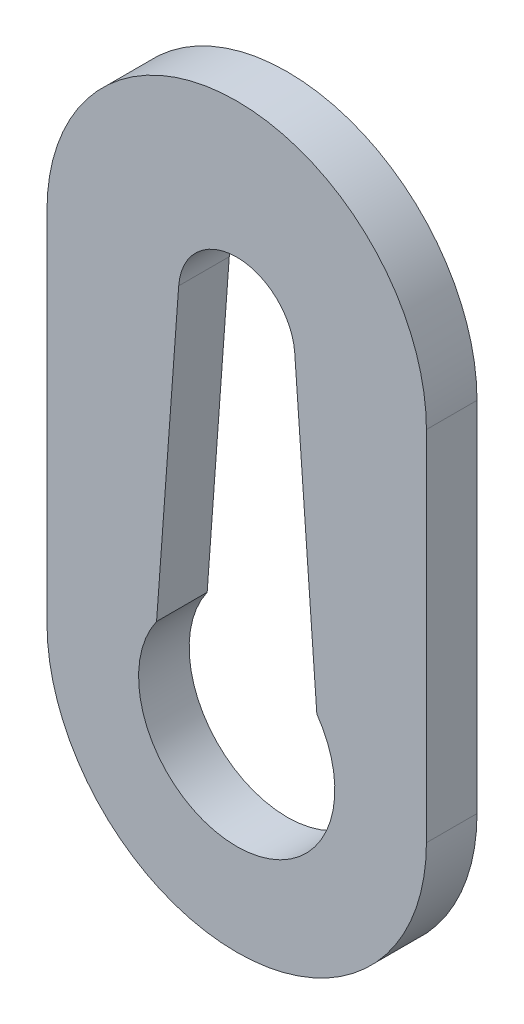
SolidWorks part; units mm, degrees
ref_plane "Front Plane" through (0, 0, 0) normal (0, 0, 1) x (1, 0, 0)
ref_plane "Top Plane" through (0, 0, 0) normal (0, 1, 0) x (1, 0, 0)
ref_plane "Right Plane" through (0, 0, 0) normal (1, 0, 0) x (0, 0, -1)
sketch "Sketch1" plane through (0, 0, 0) normal (0, 0, 1) x (1, 0, 0)
  line L0 (78.2916, 74.0996) -> (77.4175, 62.1716)
  line L1 (82.8793, 74.0996) -> (83.7534, 62.1716)
  line L3 (73.0854, 59.9315) -> (73.0854, 74.0776)
  line L5 (88.0854, 59.9315) -> (88.0854, 74.0776)
  arc A0 (73.0854, 74.0776) -> (88.0854, 74.0776) centre (80.5854, 74.0776) cw
  arc A1 (73.0854, 59.9315) -> (88.0854, 59.9315) centre (80.5854, 59.9315) ccw
  circle A2 centre (80.5854, 72.5315) radius 0.8
  circle A3 centre (80.5854, 59.9315) radius 1.85
  arc A5 (77.4175, 62.1716) -> (83.7534, 62.1716) centre (80.5854, 59.9324) ccw
  arc A6 (78.2916, 74.0996) -> (82.8793, 74.0996) centre (80.5854, 73.9315) cw
  point P21 (80.5854, 76.2315)
  point P23 (78.2916, 74.0996)
  point P26 (82.8793, 74.0996)
  point P27 (77.4175, 62.1716)
  point P28 (83.7534, 62.1716)
  point P29 (80.5854, 56.0529)
  point P30 (80.5854, 73.3315)
  dimension "D1" = 14.1462
  dimension "D2" = 15
  dimension "D4" = 2.9
extrude "Boss-Extrude1" add sketch "Sketch1" along normal blind 2 contours L3 A1 L5 A0 L0 A6 L1 A5
